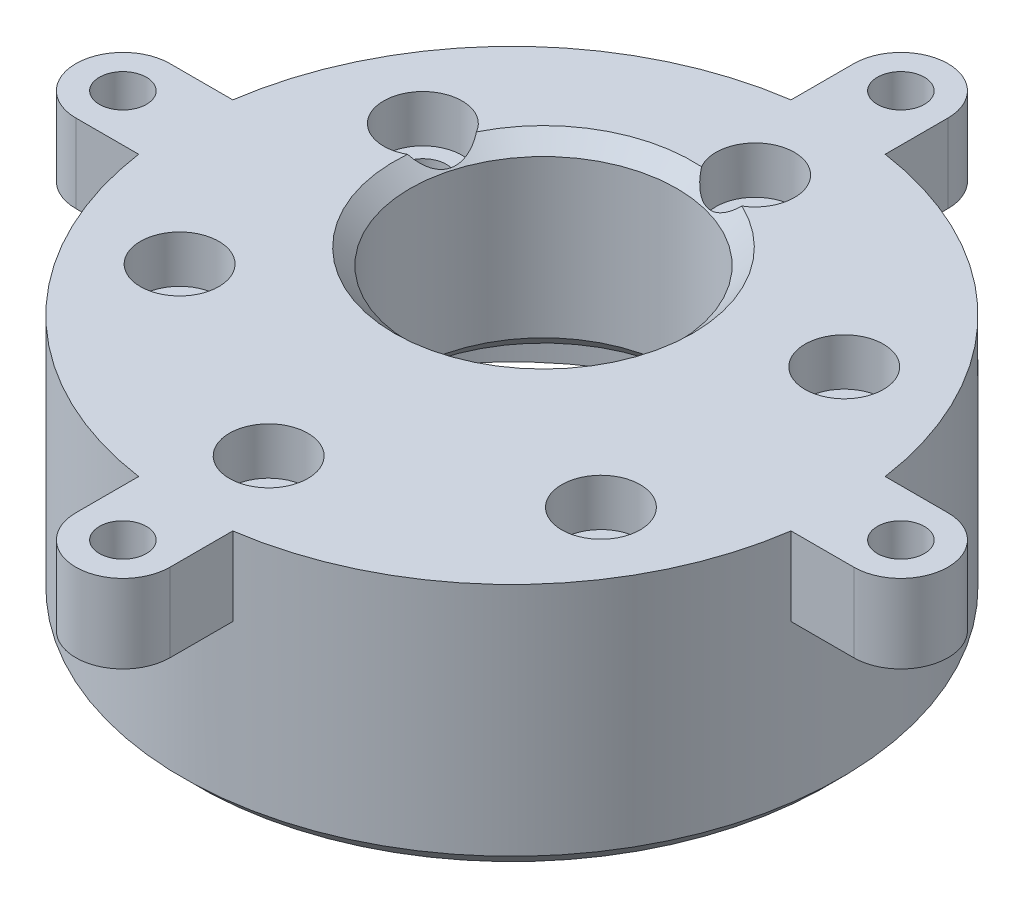
SolidWorks part; units mm, degrees
ref_plane "Front Plane" through (0, 0, 0) normal (0, 0, 1) x (1, 0, 0)
ref_plane "Top Plane" through (0, 0, 0) normal (0, 1, 0) x (1, 0, 0)
ref_plane "Right Plane" through (0, 0, 0) normal (1, 0, 0) x (0, 0, -1)
sketch "Sketch1" plane through (0, 0, 0) normal (0, 1, 0) x (1, 0, 0)
  line L0 (0, 19) -> (0, 15.5) construction
  line L1 (0, -15.5) -> (0, -19) construction
  line L2 (0, 15.5) -> (-13.4234, 7.75) construction
  line L3 (-9.5, 16.4545) -> (-7, 12.1244) construction
  line L4 (-9.5, 16.4545) -> (0, 0) construction
  circle A0 centre (0, 0) radius 19
  circle A1 centre (0, 15.5) radius 1.5
  circle A2 centre (13.4234, 7.75) radius 1.5
  circle A3 centre (13.4234, -7.75) radius 1.5
  circle A4 centre (0, -15.5) radius 1.5
  circle A5 centre (-13.4234, -7.75) radius 1.5
  circle A6 centre (-13.4234, 7.75) radius 1.5
  circle A7 centre (-2.75, 4.7631) radius 8.5
  point P6 (-6.7117, 11.625)
  dimension "D1" = 38
  dimension "D2" = 3
  dimension "D5" = 17
  dimension "D3" = 3.5
  dimension "D6" = 3.5
  dimension "D7" = 5
  dimension "D4" = 6
extrude "Boss-Extrude1" add sketch "Sketch1" along normal blind 12
sketch "Sketch2" plane through (0, 0, 0) normal (0, -1, 0) x (1, 0, 0)
  circle A0 centre (0, 0) radius 19
  circle A1 centre (0, 0) radius 19 construction
  circle A2 centre (0, 0) radius 21
  dimension "D1" = 42
extrude "Boss-Extrude2" add sketch "Sketch2" along normal blind 4 and the other way up to surface (12 mm away) other way up to face at (-13.4234, 12, 9.25)
sketch "Sketch3" plane through (0, 12, 0) normal (0, 1, 0) x (1, 0, 0)
  line L0 (-3, 24.7846) -> (-3, 20.7846)
  line L1 (3, 24.7846) -> (3, 20.7846)
  line L2 (-3, 20.7846) -> (3, 20.7846) construction
  circle A0 centre (0, 0) radius 21
  circle A1 centre (0, 0) radius 21 construction
  circle A2 centre (0, 24.7846) radius 3
  circle A3 centre (0, 24.7846) radius 1.5
  point P7 (0, 20.7846)
  circle M14 centre (0, 0) radius 21
  dimension "D1" = 6
  dimension "D2" = 3
  dimension "D3" = 4
extrude "Boss-Extrude3" add sketch "Sketch3" against normal blind 5 contours A2 A3 | A2 L0 L1 M14
chamfer "Chamfer1" distance 1 angle 45 1 edges at (0, 7, -23.2846)
pattern_circular "CirPattern2" count 4 over 360 about axis through (0, 0, 0) along (0, 1, 0) of "Chamfer1", "Boss-Extrude3"
chamfer "Chamfer3" distance 1 angle 45 3 edges at (-2.75, 12, 3.7369) (-2.75, 0, 3.7369) (0, -4, -21)
sketch "Sketch4" plane through (0, 12, 0) normal (0, 1, 0) x (1, 0, 0)
  circle A0 centre (-13.4234, -7.75) radius 2.5
  circle A1 centre (-13.4234, 7.75) radius 2.5
  circle A2 centre (0, 15.5) radius 2.5
  circle A3 centre (13.4234, 7.75) radius 2.5
  circle A4 centre (13.4234, -7.75) radius 2.5
  circle A5 centre (0, -15.5) radius 2.5
  circle A6 centre (-13.4234, -7.75) radius 1.5 construction
  circle A7 centre (-13.4234, 7.75) radius 1.5 construction
  circle A8 centre (0, -15.5) radius 1.5 construction
  circle A9 centre (13.4234, -7.75) radius 1.5 construction
  circle A10 centre (13.4234, 7.75) radius 1.5 construction
  circle A11 centre (0, 15.5) radius 1.5 construction
  point P18 (0, 0)
  point P21 (0, 0)
  dimension "D1" = 5
extrude "Cut-Extrude1" cut sketch "Sketch4" against normal blind 3
